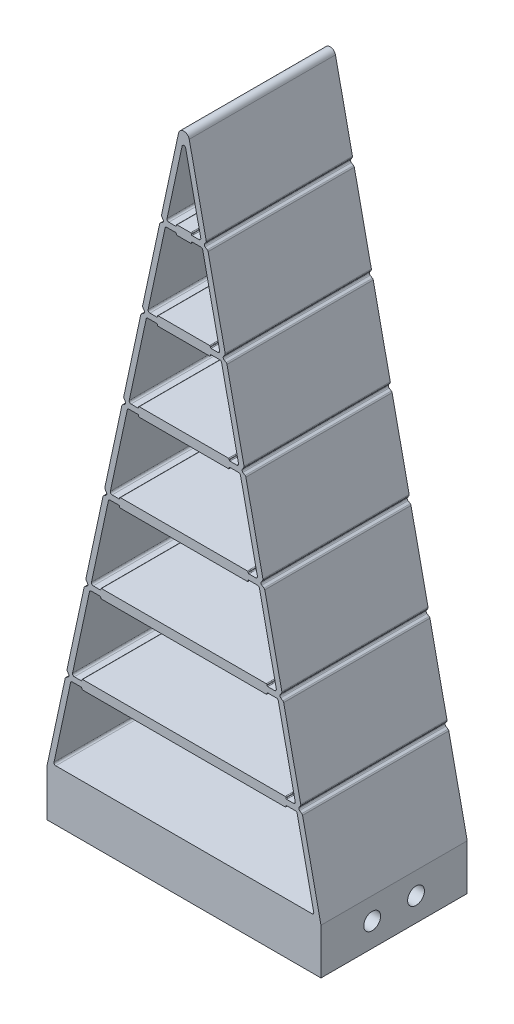
SolidWorks part; units mm, degrees
ref_plane "Front Plane" through (0, 0, 0) normal (0, 0, 1) x (1, 0, 0)
ref_plane "Top Plane" through (0, 0, 0) normal (0, 1, 0) x (1, 0, 0)
ref_plane "Right Plane" through (0, 0, 0) normal (1, 0, 0) x (0, 0, -1)
sketch "Sketch1" plane through (0, 0, 0) normal (0, 0, 1) x (1, 0, 0)
  line L15 (37.5, 0) -> (-37.5, 0)
  line L32 (-30.5831, 25.1202) -> (-27.9045, 25.1202)
  line L33 (0, 0) -> (0, 1.5) construction
  line L35 (35.6445, 1.5) -> (-35.6445, 1.5)
  line L36 (-35.6445, 1.5) -> (-30.9045, 23.6202)
  line L37 (-30.9045, 23.6202) -> (-27.9045, 23.6202)
  line L38 (30.9045, 23.6202) -> (35.6445, 1.5)
  line L39 (-27.9045, 23.6202) -> (-27.9045, 23.1202)
  line L40 (-27.9045, 23.1202) -> (27.9045, 23.1202)
  line L41 (27.9045, 23.1202) -> (27.9045, 23.6202)
  line L42 (-27.9045, 25.1202) -> (-27.9045, 25.6202)
  line L43 (-27.9045, 25.6202) -> (27.9045, 25.6202)
  line L44 (27.9045, 25.6202) -> (27.9045, 25.1202)
  line L45 (27.9045, 25.1202) -> (30.5831, 25.1202)
  line L46 (-32.1171, 25.1202) -> (32.1171, 25.1202) construction
  line L47 (27.9045, 23.6202) -> (30.9045, 23.6202)
  line L48 (-30.9045, 23.6202) -> (30.9045, 23.6202) construction
  line L49 (0, 1.5) -> (0, 23.1202) construction
  line L51 (-25.4145, 49.2403) -> (-22.7359, 49.2403)
  line L53 (-30.5831, 25.1202) -> (-25.7359, 47.7403)
  line L54 (-25.7359, 47.7403) -> (-22.7359, 47.7403)
  line L55 (25.7359, 47.7403) -> (30.5831, 25.1202)
  line L56 (-22.7359, 49.2403) -> (-22.7359, 49.7403)
  line L57 (-22.7359, 49.7403) -> (22.7359, 49.7403)
  line L58 (22.7359, 49.7403) -> (22.7359, 49.2403)
  line L59 (-22.7359, 47.7403) -> (-22.7359, 47.2403)
  line L60 (-22.7359, 47.2403) -> (22.7359, 47.2403)
  line L61 (22.7359, 47.2403) -> (22.7359, 47.7403)
  line L62 (22.7359, 49.2403) -> (25.4145, 49.2403)
  line L63 (22.7359, 47.7403) -> (25.7359, 47.7403)
  line L64 (0, 143.7209) -> (0, 146.2209) construction
  line L65 (0, 23.1202) -> (0, 25.6202) construction
  line L66 (-37.5, 0) -> (0, 175)
  line L67 (-20.2458, 73.3605) -> (-17.5673, 73.3605)
  line L69 (-25.4145, 49.2403) -> (-20.5673, 71.8605)
  line L70 (-20.5673, 71.8605) -> (-17.5673, 71.8605)
  line L71 (20.5673, 71.8605) -> (25.4145, 49.2403)
  line L72 (-17.5673, 71.8605) -> (-17.5673, 71.3605)
  line L73 (-17.5673, 71.3605) -> (17.5673, 71.3605)
  line L74 (17.5673, 71.3605) -> (17.5673, 71.8605)
  line L75 (-17.5673, 73.3605) -> (-17.5673, 73.8605)
  line L76 (-17.5673, 73.8605) -> (17.5673, 73.8605)
  line L77 (17.5673, 73.8605) -> (17.5673, 73.3605)
  line L78 (17.5673, 73.3605) -> (20.2458, 73.3605)
  line L79 (17.5673, 71.8605) -> (20.5673, 71.8605)
  line L80 (0, 25.6202) -> (0, 47.2403) construction
  line L81 (0, 49.7403) -> (0, 71.3605) construction
  line L82 (0, 119.6008) -> (0, 122.1008) construction
  line L83 (-37.5, 0) -> (-32.1171, 25.1202) construction
  line L84 (32.1171, 25.1202) -> (37.5, 0) construction
  line L85 (0, 175) -> (37.5, 0)
  line L87 (-15.0772, 97.4806) -> (-12.3987, 97.4806)
  line L89 (-20.2458, 73.3605) -> (-15.3987, 95.9806)
  line L90 (-15.3987, 95.9806) -> (-12.3987, 95.9806)
  line L91 (15.3987, 95.9806) -> (20.2458, 73.3605)
  line L92 (-12.3987, 95.9806) -> (-12.3987, 95.4806)
  line L93 (-12.3987, 95.4806) -> (12.3987, 95.4806)
  line L94 (12.3987, 95.4806) -> (12.3987, 95.9806)
  line L95 (-12.3987, 97.4806) -> (-12.3987, 97.9806)
  line L96 (-12.3987, 97.9806) -> (12.3987, 97.9806)
  line L97 (12.3987, 97.9806) -> (12.3987, 97.4806)
  line L98 (12.3987, 97.4806) -> (15.0772, 97.4806)
  line L99 (12.3987, 95.9806) -> (15.3987, 95.9806)
  line L100 (0, 95.4806) -> (0, 97.9806) construction
  line L101 (0, 73.8605) -> (0, 95.4806) construction
  line L102 (0, 71.3605) -> (0, 73.8605) construction
  line L103 (-9.9086, 121.6008) -> (-7.2301, 121.6008)
  line L104 (0, 97.9806) -> (0, 119.6008) construction
  line L105 (-15.0772, 97.4806) -> (-10.2301, 120.1008)
  line L106 (-10.2301, 120.1008) -> (-7.2301, 120.1008)
  line L107 (10.2301, 120.1008) -> (15.0772, 97.4806)
  line L108 (-7.2301, 120.1008) -> (-7.2301, 119.6008)
  line L109 (-7.2301, 119.6008) -> (7.2301, 119.6008)
  line L110 (7.2301, 119.6008) -> (7.2301, 120.1008)
  line L111 (-7.2301, 121.6008) -> (-7.2301, 122.1008)
  line L112 (-7.2301, 122.1008) -> (7.2301, 122.1008)
  line L113 (7.2301, 122.1008) -> (7.2301, 121.6008)
  line L114 (7.2301, 121.6008) -> (9.9086, 121.6008)
  line L115 (7.2301, 120.1008) -> (10.2301, 120.1008)
  line L118 (0, 122.1008) -> (0, 143.7209) construction
  line L119 (-9.9086, 121.6008) -> (-5.0615, 144.2209)
  line L120 (5.0615, 144.2209) -> (9.9086, 121.6008)
  line L126 (2.0615, 143.7209) -> (-2.0615, 143.7209)
  line L127 (-2.0615, 143.7209) -> (-2.0615, 144.2209)
  line L128 (-2.0615, 144.2209) -> (-5.0615, 144.2209)
  line L130 (2.0615, 143.7209) -> (2.0615, 144.2209)
  line L131 (2.0615, 144.2209) -> (5.0615, 144.2209)
  line L132 (-4.74, 145.7209) -> (-2.0615, 145.7209)
  line L133 (-2.0615, 145.7209) -> (-2.0615, 146.2209)
  line L134 (-2.0615, 146.2209) -> (2.0615, 146.2209)
  line L135 (2.0615, 146.2209) -> (2.0615, 145.7209)
  line L136 (2.0615, 145.7209) -> (4.74, 145.7209)
  line L137 (0, 47.2403) -> (0, 49.7403) construction
  line L138 (4.74, 145.7209) -> (0, 167.8411)
  line L139 (-4.74, 145.7209) -> (0, 167.8411)
  line L140 (0, 146.2209) -> (0, 167.8411) construction
  point P3 (0, 0)
  point P4 (0, 0)
  point P90 (0, 143.7209)
  dimension "D2" = 175
  dimension "D1" = 0.5
  dimension "D4" = 3
  dimension "D5" = 75
  dimension "D3" = 1.5
extrude "Boss-Extrude1" add sketch "Sketch1" along normal blind 40
sketch "Sketch6" plane through (0, 0, 40) normal (0, 0, 1) x (1, 0, 0)
  line L0 (-32.0009, 25.6623) -> (-31.2327, 24.4749)
  line L1 (0, 175) -> (-37.5, 0) construction
  line L2 (-31.2327, 24.4749) -> (-32.42, 23.7066)
  line L3 (-32.42, 23.7066) -> (-32.0009, 25.6623)
  line L4 (-30.5831, 25.1202) -> (-30.9045, 23.6202) construction
  line L5 (-30.9045, 23.6202) -> (-35.6445, 1.5) construction
  line L6 (-32.2105, 24.6844) -> (-31.7216, 24.5797) construction
  line L7 (-31.7216, 24.5797) -> (-31.2327, 24.4749) construction
  line L8 (-31.2327, 24.4749) -> (-30.7438, 24.3702) construction
  line L9 (-26.8323, 49.7824) -> (-26.0641, 48.5951)
  line L10 (-26.0641, 48.5951) -> (-27.2514, 47.8268)
  line L11 (-27.2514, 47.8268) -> (-26.8323, 49.7824)
  line L12 (-25.4145, 49.2403) -> (-25.7359, 47.7403) construction
  line L13 (-27.0419, 48.8046) -> (-26.553, 48.6998) construction
  line L14 (-26.553, 48.6998) -> (-26.0641, 48.5951) construction
  line L15 (-26.0641, 48.5951) -> (-25.5752, 48.4903) construction
  line L16 (-21.6637, 73.9026) -> (-20.8955, 72.7152)
  line L17 (-20.8955, 72.7152) -> (-22.0828, 71.947)
  line L18 (-22.0828, 71.947) -> (-21.6637, 73.9026)
  line L19 (-20.2458, 73.3605) -> (-20.5673, 71.8605) construction
  line L20 (-21.8733, 72.9248) -> (-21.3844, 72.82) construction
  line L21 (-21.3844, 72.82) -> (-20.8955, 72.7152) construction
  line L22 (-20.8955, 72.7152) -> (-20.4066, 72.6105) construction
  line L23 (-16.4951, 98.0227) -> (-15.7269, 96.8354)
  line L24 (-15.7269, 96.8354) -> (-16.9142, 96.0671)
  line L25 (-16.9142, 96.0671) -> (-16.4951, 98.0227)
  line L26 (-15.0772, 97.4806) -> (-15.3987, 95.9806) construction
  line L27 (-16.7047, 97.0449) -> (-16.2158, 96.9402) construction
  line L28 (-16.2158, 96.9402) -> (-15.7269, 96.8354) construction
  line L29 (-15.7269, 96.8354) -> (-15.238, 96.7306) construction
  line L30 (-11.3265, 122.1429) -> (-10.5583, 120.9555)
  line L31 (-10.5583, 120.9555) -> (-11.7456, 120.1873)
  line L32 (-11.7456, 120.1873) -> (-11.3265, 122.1429)
  line L33 (-9.9086, 121.6008) -> (-10.2301, 120.1008) construction
  line L34 (-11.5361, 121.1651) -> (-11.0472, 121.0603) construction
  line L35 (-11.0472, 121.0603) -> (-10.5583, 120.9555) construction
  line L36 (-10.5583, 120.9555) -> (-10.0694, 120.8508) construction
  line L37 (-6.1579, 146.263) -> (-5.3896, 145.0757)
  line L38 (-5.3896, 145.0757) -> (-6.577, 144.3074)
  line L39 (-6.577, 144.3074) -> (-6.1579, 146.263)
  line L40 (-4.74, 145.7209) -> (-5.0615, 144.2209) construction
  line L41 (-6.3675, 145.2852) -> (-5.8786, 145.1805) construction
  line L42 (-5.8786, 145.1805) -> (-5.3896, 145.0757) construction
  line L43 (-5.3896, 145.0757) -> (-4.9007, 144.9709) construction
  line L44 (0, 0) -> (0, 175) construction
  line L45 (5.3896, 145.0757) -> (4.9007, 144.9709) construction
  line L46 (5.8786, 145.1805) -> (5.3896, 145.0757) construction
  line L47 (6.3675, 145.2852) -> (5.8786, 145.1805) construction
  line L48 (4.74, 145.7209) -> (5.0615, 144.2209) construction
  line L49 (10.5583, 120.9555) -> (10.0694, 120.8508) construction
  line L50 (11.0472, 121.0603) -> (10.5583, 120.9555) construction
  line L51 (11.5361, 121.1651) -> (11.0472, 121.0603) construction
  line L52 (9.9086, 121.6008) -> (10.2301, 120.1008) construction
  line L53 (15.7269, 96.8354) -> (15.238, 96.7306) construction
  line L54 (16.2158, 96.9402) -> (15.7269, 96.8354) construction
  line L55 (16.7047, 97.0449) -> (16.2158, 96.9402) construction
  line L56 (15.0772, 97.4806) -> (15.3987, 95.9806) construction
  line L57 (20.8955, 72.7152) -> (20.4066, 72.6105) construction
  line L58 (21.3844, 72.82) -> (20.8955, 72.7152) construction
  line L59 (21.8733, 72.9248) -> (21.3844, 72.82) construction
  line L60 (20.2458, 73.3605) -> (20.5673, 71.8605) construction
  line L61 (26.0641, 48.5951) -> (25.5752, 48.4903) construction
  line L62 (26.553, 48.6998) -> (26.0641, 48.5951) construction
  line L63 (27.0419, 48.8046) -> (26.553, 48.6998) construction
  line L64 (25.4145, 49.2403) -> (25.7359, 47.7403) construction
  line L65 (31.2327, 24.4749) -> (30.7438, 24.3702) construction
  line L66 (31.7216, 24.5797) -> (31.2327, 24.4749) construction
  line L67 (32.2105, 24.6844) -> (31.7216, 24.5797) construction
  line L68 (30.5831, 25.1202) -> (30.9045, 23.6202) construction
  line L69 (6.577, 144.3074) -> (6.1579, 146.263)
  line L70 (5.3896, 145.0757) -> (6.577, 144.3074)
  line L71 (6.1579, 146.263) -> (5.3896, 145.0757)
  line L72 (11.7456, 120.1873) -> (11.3265, 122.1429)
  line L73 (10.5583, 120.9555) -> (11.7456, 120.1873)
  line L74 (11.3265, 122.1429) -> (10.5583, 120.9555)
  line L75 (16.9142, 96.0671) -> (16.4951, 98.0227)
  line L76 (15.7269, 96.8354) -> (16.9142, 96.0671)
  line L77 (16.4951, 98.0227) -> (15.7269, 96.8354)
  line L78 (22.0828, 71.947) -> (21.6637, 73.9026)
  line L79 (20.8955, 72.7152) -> (22.0828, 71.947)
  line L80 (21.6637, 73.9026) -> (20.8955, 72.7152)
  line L81 (27.2514, 47.8268) -> (26.8323, 49.7824)
  line L82 (26.0641, 48.5951) -> (27.2514, 47.8268)
  line L83 (26.8323, 49.7824) -> (26.0641, 48.5951)
  line L84 (32.42, 23.7066) -> (32.0009, 25.6623)
  line L85 (31.2327, 24.4749) -> (32.42, 23.7066)
  line L86 (32.0009, 25.6623) -> (31.2327, 24.4749)
  dimension "D1" = 2
  dimension "D2" = 6
extrude "Cut-Extrude3" cut sketch "Sketch6" against normal through all
fillet "Fillet2" radius 1.5 1 edges at (0, 175, 20)
fillet "Fillet3" radius 0.5 27 edges at (30.5831, 25.1202, 20) (30.9045, 23.6202, 20) (-30.9045, 23.6202, 20) (-30.5831, 25.1202, 20) (25.7359, 47.7403, 20) (25.4145, 49.2403, 20) (-25.7359, 47.7403, 20) (-25.4145, 49.2403, 20) (-20.5673, 71.8605, 20) (20.2458, 73.3605, 20) (20.5673, 71.8605, 20) (-20.2458, 73.3605, 20) (15.3987, 95.9806, 20) (-15.3987, 95.9806, 20) (15.0772, 97.4806, 20) (-15.0772, 97.4806, 20) (10.2301, 120.1008, 20) (-10.2301, 120.1008, 20) (5.0615, 144.2209, 20) (-5.0615, 144.2209, 20) (9.9086, 121.6008, 20) (-9.9086, 121.6008, 20) (4.74, 145.7209, 20) (-4.74, 145.7209, 20) (0, 167.8411, 20) (35.6445, 1.5, 20) (-35.6445, 1.5, 20)
fillet "Fillet4" radius 0.2 48 edges at (-27.9045, 23.6202, 20) (-27.9045, 25.1202, 20) (-27.9045, 23.1202, 20) (-27.9045, 25.6202, 20) (27.9045, 23.1202, 20) (27.9045, 23.6202, 20) (27.9045, 25.6202, 20) (27.9045, 25.1202, 20) (22.7359, 49.7403, 20) (22.7359, 49.2403, 20) (22.7359, 47.7403, 20) (22.7359, 47.2403, 20) (-22.7359, 47.7403, 20) (-22.7359, 47.2403, 20) (-22.7359, 49.2403, 20) (-22.7359, 49.7403, 20) (-17.5673, 73.8605, 20) (-17.5673, 73.3605, 20) (-17.5673, 71.3605, 20) (-17.5673, 71.8605, 20) (17.5673, 71.8605, 20) (17.5673, 73.8605, 20) (17.5673, 73.3605, 20) (17.5673, 71.3605, 20) (12.3987, 95.9806, 20) (12.3987, 95.4806, 20) (12.3987, 97.4806, 20) (12.3987, 97.9806, 20) (-12.3987, 97.9806, 20) (-12.3987, 97.4806, 20) (-12.3987, 95.9806, 20) (-12.3987, 95.4806, 20) (-2.0615, 144.2209, 20) (-2.0615, 143.7209, 20) (2.0615, 143.7209, 20) (2.0615, 144.2209, 20) (2.0615, 146.2209, 20) (2.0615, 145.7209, 20) (-2.0615, 146.2209, 20) (-2.0615, 145.7209, 20) (7.2301, 122.1008, 20) (7.2301, 121.6008, 20) (7.2301, 120.1008, 20) (7.2301, 119.6008, 20) (-7.2301, 120.1008, 20) (-7.2301, 119.6008, 20) (-7.2301, 122.1008, 20) (-7.2301, 121.6008, 20)
fillet "Fillet5" radius 0.5 36 edges at (32.0009, 25.6623, 20) (31.2327, 24.4749, 20) (32.42, 23.7066, 20) (26.8323, 49.7824, 20) (26.0641, 48.5951, 20) (27.2514, 47.8268, 20) (21.6637, 73.9026, 20) (20.8955, 72.7152, 20) (22.0828, 71.947, 20) (16.4951, 98.0227, 20) (15.7269, 96.8354, 20) (16.9142, 96.0671, 20) (11.3265, 122.1429, 20) (10.5583, 120.9555, 20) (11.7456, 120.1873, 20) (6.1579, 146.263, 20) (5.3896, 145.0757, 20) (6.577, 144.3074, 20) (-6.1579, 146.263, 20) (-5.3896, 145.0757, 20) (-6.577, 144.3074, 20) (-11.3265, 122.1429, 20) (-10.5583, 120.9555, 20) (-11.7456, 120.1873, 20) (-16.4951, 98.0227, 20) (-15.7269, 96.8354, 20) (-16.9142, 96.0671, 20) (-21.6637, 73.9026, 20) (-20.8955, 72.7152, 20) (-22.0828, 71.947, 20) (-26.8323, 49.7824, 20) (-26.0641, 48.5951, 20) (-27.2514, 47.8268, 20) (-32.0009, 25.6623, 20) (-31.2327, 24.4749, 20) (-32.42, 23.7066, 20)
sketch "Sketch7" [suppressed] plane through (0, 0, 20) normal (0, 0, 1) x (1, 0, 0)
  line L0 (-37.5, 0) -> (-37.5, -3.5)
  line L1 (-37.5, -3.5) -> (37.5, -3.5)
  line L2 (37.5, -3.5) -> (37.5, 0)
  line L3 (-37.5, 0) -> (37.5, 0)
  dimension "D1" = 3.5
extrude "Boss-Extrude3" [suppressed] add sketch "Sketch7" against normal up to surface (20 mm away)
sketch "Sketch3" plane through (0, 0, 0) normal (0, 0, 1) x (1, 0, 0)
  line L0 (-37.5, 0) -> (-37.5, -12.5)
  line L1 (-37.5, -12.5) -> (37.5, -12.5)
  line L2 (37.5, -12.5) -> (37.5, 0)
  line L3 (-37.5, 0) -> (37.5, 0)
  dimension "D1" = 12.5
extrude "Boss-Extrude2" add sketch "Sketch3" along normal up to surface (40 mm away) up to face at (0, 84.8977, 40)
sketch "Sketch5" plane through (0, -12.5, 0) normal (0, -1, 0) x (1, 0, 0)
  line L2 (21, 30.75) -> (21, 9.25)
  line L4 (27.5, 30.75) -> (27.5, 9.25)
  line L6 (27.5, 20) -> (37.5, 20) construction
  line L7 (37.5, 40) -> (37.5, 0) construction
  line L8 (21, 30.75) -> (27.5, 30.75)
  line L9 (21, 9.25) -> (27.5, 9.25)
  dimension "D1" = 10
  dimension "D2" = 6.5
  dimension "D3" = 21.5
extrude "Cut-Extrude2" cut sketch "Sketch5" against normal blind 12
sketch "Sketch4" plane through (37.5, 0, 0) normal (1, 0, 0) x (0, 0, -1)
  line L0 (-20, 0) -> (-20, -6) construction
  line L1 (-40, 0) -> (0, 0) construction
  line L2 (-20, -6) -> (-26, -6) construction
  line L3 (-20, -6) -> (-14, -6) construction
  circle A0 centre (-26, -6) radius 2.3
  circle A1 centre (-14, -6) radius 2.3
  dimension "D1" = 4.6
  dimension "D2" = 6
  dimension "D3" = 6
extrude "Cut-Extrude1" cut sketch "Sketch4" against normal through all
